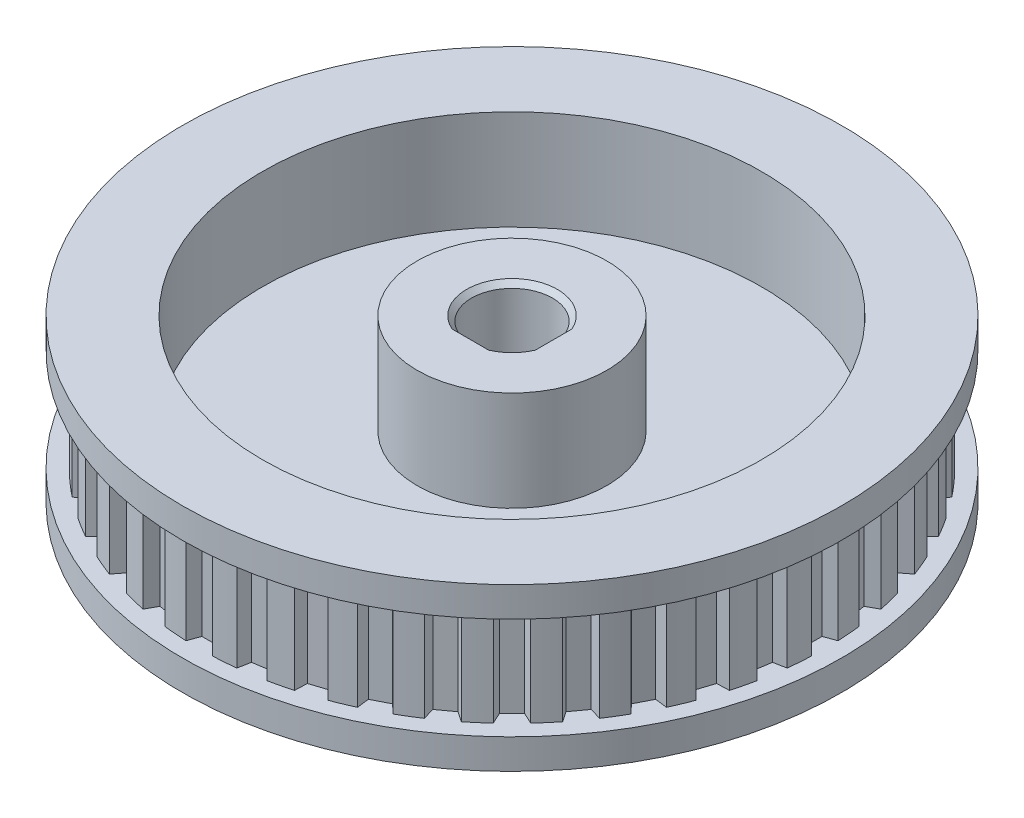
SolidWorks part; units mm, degrees
ref_plane "Спереди" through (0, 0, 0) normal (0, 0, 1) x (1, 0, 0)
ref_plane "Сверху" through (0, 0, 0) normal (0, 1, 0) x (1, 0, 0)
ref_plane "Справа" through (0, 0, 0) normal (1, 0, 0) x (0, 0, -1)
sketch "Эскиз1" plane through (0, 0, 0) normal (0, 1, 0) x (1, 0, 0)
  line L0 (0, 32.35) -> (0, 0) construction
  line L1 (-0.9, 30.15) -> (0.9, 30.15)
  line L2 (-0.9, 30.15) -> (-1.3265, 31.3219)
  line L3 (0.9, 30.15) -> (1.3265, 31.3219)
  line L4 (3.8276, 29.9196) -> (3.5896, 31.1438)
  line L5 (3.8276, 29.9196) -> (5.6054, 29.638)
  line L6 (5.6054, 29.638) -> (6.21, 30.7288)
  line L7 (8.4609, 28.9525) -> (8.4174, 30.1988)
  line L8 (8.4609, 28.9525) -> (10.1728, 28.3962)
  line L9 (10.1728, 28.3962) -> (10.9406, 29.379)
  line L10 (12.8859, 27.2724) -> (13.0379, 28.5103)
  line L11 (12.8859, 27.2724) -> (14.4897, 26.4553)
  line L12 (14.4897, 26.4553) -> (15.4018, 27.3058)
  line L13 (16.9936, 24.9209) -> (17.3374, 26.1197)
  line L14 (16.9936, 24.9209) -> (18.4498, 23.8629)
  line L15 (18.4498, 23.8629) -> (19.4838, 24.5602)
  line L16 (20.6829, 21.9557) -> (21.2099, 23.086)
  line L17 (20.6829, 21.9557) -> (21.9557, 20.6829)
  line L18 (21.9557, 20.6829) -> (23.086, 21.2099)
  line L19 (23.8629, 18.4498) -> (24.5602, 19.4838)
  line L20 (23.8629, 18.4498) -> (24.9209, 16.9936)
  line L21 (24.9209, 16.9936) -> (26.1197, 17.3374)
  line L22 (26.4553, 14.4897) -> (27.3058, 15.4018)
  line L23 (26.4553, 14.4897) -> (27.2724, 12.8859)
  line L24 (27.2724, 12.8859) -> (28.5103, 13.0379)
  line L25 (28.3962, 10.1728) -> (29.379, 10.9406)
  line L26 (28.3962, 10.1728) -> (28.9525, 8.4609)
  line L27 (28.9525, 8.4609) -> (30.1988, 8.4174)
  line L28 (29.638, 5.6054) -> (30.7288, 6.21)
  line L29 (29.638, 5.6054) -> (29.9196, 3.8276)
  line L30 (29.9196, 3.8276) -> (31.1438, 3.5896)
  line L31 (30.15, 0.9) -> (31.3219, 1.3265)
  line L32 (30.15, 0.9) -> (30.15, -0.9)
  line L33 (30.15, -0.9) -> (31.3219, -1.3265)
  line L34 (29.9196, -3.8276) -> (31.1438, -3.5896)
  line L35 (29.9196, -3.8276) -> (29.638, -5.6054)
  line L36 (29.638, -5.6054) -> (30.7288, -6.21)
  line L37 (28.9525, -8.4609) -> (30.1988, -8.4174)
  line L38 (28.9525, -8.4609) -> (28.3962, -10.1728)
  line L39 (28.3962, -10.1728) -> (29.379, -10.9406)
  line L40 (27.2724, -12.8859) -> (28.5103, -13.0379)
  line L41 (27.2724, -12.8859) -> (26.4553, -14.4897)
  line L42 (26.4553, -14.4897) -> (27.3058, -15.4018)
  line L43 (24.9209, -16.9936) -> (26.1197, -17.3374)
  line L44 (24.9209, -16.9936) -> (23.8629, -18.4498)
  line L45 (23.8629, -18.4498) -> (24.5602, -19.4838)
  line L46 (21.9557, -20.6829) -> (23.086, -21.2099)
  line L47 (21.9557, -20.6829) -> (20.6829, -21.9557)
  line L48 (20.6829, -21.9557) -> (21.2099, -23.086)
  line L49 (18.4498, -23.8629) -> (19.4838, -24.5602)
  line L50 (18.4498, -23.8629) -> (16.9936, -24.9209)
  line L51 (16.9936, -24.9209) -> (17.3374, -26.1197)
  line L52 (14.4897, -26.4553) -> (15.4018, -27.3058)
  line L53 (14.4897, -26.4553) -> (12.8859, -27.2724)
  line L54 (12.8859, -27.2724) -> (13.0379, -28.5103)
  line L55 (10.1728, -28.3962) -> (10.9406, -29.379)
  line L56 (10.1728, -28.3962) -> (8.4609, -28.9525)
  line L57 (8.4609, -28.9525) -> (8.4174, -30.1988)
  line L58 (5.6054, -29.638) -> (6.21, -30.7288)
  line L59 (5.6054, -29.638) -> (3.8276, -29.9196)
  line L60 (3.8276, -29.9196) -> (3.5896, -31.1438)
  line L61 (0.9, -30.15) -> (1.3265, -31.3219)
  line L62 (0.9, -30.15) -> (-0.9, -30.15)
  line L63 (-0.9, -30.15) -> (-1.3265, -31.3219)
  line L64 (-3.8276, -29.9196) -> (-3.5896, -31.1438)
  line L65 (-3.8276, -29.9196) -> (-5.6054, -29.638)
  line L66 (-5.6054, -29.638) -> (-6.21, -30.7288)
  line L67 (-8.4609, -28.9525) -> (-8.4174, -30.1988)
  line L68 (-8.4609, -28.9525) -> (-10.1728, -28.3962)
  line L69 (-10.1728, -28.3962) -> (-10.9406, -29.379)
  line L70 (-12.8859, -27.2724) -> (-13.0379, -28.5103)
  line L71 (-12.8859, -27.2724) -> (-14.4897, -26.4553)
  line L72 (-14.4897, -26.4553) -> (-15.4018, -27.3058)
  line L73 (-16.9936, -24.9209) -> (-17.3374, -26.1197)
  line L74 (-16.9936, -24.9209) -> (-18.4498, -23.8629)
  line L75 (-18.4498, -23.8629) -> (-19.4838, -24.5602)
  line L76 (-20.6829, -21.9557) -> (-21.2099, -23.086)
  line L77 (-20.6829, -21.9557) -> (-21.9557, -20.6829)
  line L78 (-21.9557, -20.6829) -> (-23.086, -21.2099)
  line L79 (-23.8629, -18.4498) -> (-24.5602, -19.4838)
  line L80 (-23.8629, -18.4498) -> (-24.9209, -16.9936)
  line L81 (-24.9209, -16.9936) -> (-26.1197, -17.3374)
  line L82 (-26.4553, -14.4897) -> (-27.3058, -15.4018)
  line L83 (-26.4553, -14.4897) -> (-27.2724, -12.8859)
  line L84 (-27.2724, -12.8859) -> (-28.5103, -13.0379)
  line L85 (-28.3962, -10.1728) -> (-29.379, -10.9406)
  line L86 (-28.3962, -10.1728) -> (-28.9525, -8.4609)
  line L87 (-28.9525, -8.4609) -> (-30.1988, -8.4174)
  line L88 (-29.638, -5.6054) -> (-30.7288, -6.21)
  line L89 (-29.638, -5.6054) -> (-29.9196, -3.8276)
  line L90 (-29.9196, -3.8276) -> (-31.1438, -3.5896)
  line L91 (-30.15, -0.9) -> (-31.3219, -1.3265)
  line L92 (-30.15, -0.9) -> (-30.15, 0.9)
  line L93 (-30.15, 0.9) -> (-31.3219, 1.3265)
  line L94 (-29.9196, 3.8276) -> (-31.1438, 3.5896)
  line L95 (-29.9196, 3.8276) -> (-29.638, 5.6054)
  line L96 (-29.638, 5.6054) -> (-30.7288, 6.21)
  line L97 (-28.9525, 8.4609) -> (-30.1988, 8.4174)
  line L98 (-28.9525, 8.4609) -> (-28.3962, 10.1728)
  line L99 (-28.3962, 10.1728) -> (-29.379, 10.9406)
  line L100 (-27.2724, 12.8859) -> (-28.5103, 13.0379)
  line L101 (-27.2724, 12.8859) -> (-26.4553, 14.4897)
  line L102 (-26.4553, 14.4897) -> (-27.3058, 15.4018)
  line L103 (-24.9209, 16.9936) -> (-26.1197, 17.3374)
  line L104 (-24.9209, 16.9936) -> (-23.8629, 18.4498)
  line L105 (-23.8629, 18.4498) -> (-24.5602, 19.4838)
  line L106 (-21.9557, 20.6829) -> (-23.086, 21.2099)
  line L107 (-21.9557, 20.6829) -> (-20.6829, 21.9557)
  line L108 (-20.6829, 21.9557) -> (-21.2099, 23.086)
  line L109 (-18.4498, 23.8629) -> (-19.4838, 24.5602)
  line L110 (-18.4498, 23.8629) -> (-16.9936, 24.9209)
  line L111 (-16.9936, 24.9209) -> (-17.3374, 26.1197)
  line L112 (-14.4897, 26.4553) -> (-15.4018, 27.3058)
  line L113 (-14.4897, 26.4553) -> (-12.8859, 27.2724)
  line L114 (-12.8859, 27.2724) -> (-13.0379, 28.5103)
  line L115 (-10.1728, 28.3962) -> (-10.9406, 29.379)
  line L116 (-10.1728, 28.3962) -> (-8.4609, 28.9525)
  line L117 (-8.4609, 28.9525) -> (-8.4174, 30.1988)
  line L118 (-5.6054, 29.638) -> (-6.21, 30.7288)
  line L119 (-5.6054, 29.638) -> (-3.8276, 29.9196)
  line L120 (-3.8276, 29.9196) -> (-3.5896, 31.1438)
  circle A0 centre (0, 0) radius 30.15 construction
  circle A1 centre (0, 0) radius 32.35 construction
  circle A2 centre (0, 0) radius 31.85 construction
  circle A3 centre (0, 0) radius 31.35 construction
  arc A4 (-3.5896, 31.1438) -> (-1.3265, 31.3219) centre (0, 0) cw
  arc A5 (1.3265, 31.3219) -> (3.5896, 31.1438) centre (0, 0) cw
  arc A6 (6.21, 30.7288) -> (8.4174, 30.1988) centre (0, 0) cw
  arc A7 (10.9406, 29.379) -> (13.0379, 28.5103) centre (0, 0) cw
  arc A8 (15.4018, 27.3058) -> (17.3374, 26.1197) centre (0, 0) cw
  arc A9 (19.4838, 24.5602) -> (21.2099, 23.086) centre (0, 0) cw
  arc A10 (23.086, 21.2099) -> (24.5602, 19.4838) centre (0, 0) cw
  arc A11 (26.1197, 17.3374) -> (27.3058, 15.4018) centre (0, 0) cw
  arc A12 (28.5103, 13.0379) -> (29.379, 10.9406) centre (0, 0) cw
  arc A13 (30.1988, 8.4174) -> (30.7288, 6.21) centre (0, 0) cw
  arc A14 (31.1438, 3.5896) -> (31.3219, 1.3265) centre (0, 0) cw
  arc A15 (31.3219, -1.3265) -> (31.1438, -3.5896) centre (0, 0) cw
  arc A16 (30.7288, -6.21) -> (30.1988, -8.4174) centre (0, 0) cw
  arc A17 (29.379, -10.9406) -> (28.5103, -13.0379) centre (0, 0) cw
  arc A18 (27.3058, -15.4018) -> (26.1197, -17.3374) centre (0, 0) cw
  arc A19 (24.5602, -19.4838) -> (23.086, -21.2099) centre (0, 0) cw
  arc A20 (21.2099, -23.086) -> (19.4838, -24.5602) centre (0, 0) cw
  arc A21 (17.3374, -26.1197) -> (15.4018, -27.3058) centre (0, 0) cw
  arc A22 (13.0379, -28.5103) -> (10.9406, -29.379) centre (0, 0) cw
  arc A23 (8.4174, -30.1988) -> (6.21, -30.7288) centre (0, 0) cw
  arc A24 (3.5896, -31.1438) -> (1.3265, -31.3219) centre (0, 0) cw
  arc A25 (-1.3265, -31.3219) -> (-3.5896, -31.1438) centre (0, 0) cw
  arc A26 (-6.21, -30.7288) -> (-8.4174, -30.1988) centre (0, 0) cw
  arc A27 (-10.9406, -29.379) -> (-13.0379, -28.5103) centre (0, 0) cw
  arc A28 (-15.4018, -27.3058) -> (-17.3374, -26.1197) centre (0, 0) cw
  arc A29 (-19.4838, -24.5602) -> (-21.2099, -23.086) centre (0, 0) cw
  arc A30 (-23.086, -21.2099) -> (-24.5602, -19.4838) centre (0, 0) cw
  arc A31 (-26.1197, -17.3374) -> (-27.3058, -15.4018) centre (0, 0) cw
  arc A32 (-28.5103, -13.0379) -> (-29.379, -10.9406) centre (0, 0) cw
  arc A33 (-30.1988, -8.4174) -> (-30.7288, -6.21) centre (0, 0) cw
  arc A34 (-31.1438, -3.5896) -> (-31.3219, -1.3265) centre (0, 0) cw
  arc A35 (-31.3219, 1.3265) -> (-31.1438, 3.5896) centre (0, 0) cw
  arc A36 (-30.7288, 6.21) -> (-30.1988, 8.4174) centre (0, 0) cw
  arc A37 (-29.379, 10.9406) -> (-28.5103, 13.0379) centre (0, 0) cw
  arc A38 (-27.3058, 15.4018) -> (-26.1197, 17.3374) centre (0, 0) cw
  arc A39 (-24.5602, 19.4838) -> (-23.086, 21.2099) centre (0, 0) cw
  arc A40 (-21.2099, 23.086) -> (-19.4838, 24.5602) centre (0, 0) cw
  arc A41 (-17.3374, 26.1197) -> (-15.4018, 27.3058) centre (0, 0) cw
  arc A42 (-13.0379, 28.5103) -> (-10.9406, 29.379) centre (0, 0) cw
  arc A43 (-8.4174, 30.1988) -> (-6.21, 30.7288) centre (0, 0) cw
  point P6 (0, 30.15)
  dimension "D1" = 63.7
  dimension "D2" = 64.7
  dimension "D3" = 60.3
  dimension "D4" = 62.7
  dimension "D5" = 1.8
  dimension "D6" = 20
  dimension "D7" = 20
extrude "Вытянуть1" add sketch "Эскиз1" along normal blind 10.2
sketch "Эскиз2" plane through (0, 10.2, 0) normal (0, 1, 0) x (1, 0, 0)
  circle A0 centre (0, 0) radius 33
  dimension "D1" = 66
extrude "Вытянуть2" add sketch "Эскиз2" along normal blind 3
sketch "Эскиз3" plane through (0, 0, 0) normal (0, -1, 0) x (1, 0, 0)
  circle A0 centre (0, 0) radius 33
  circle A1 centre (0, 0) radius 33 construction
extrude "Вытянуть3" add sketch "Эскиз3" along normal blind 3
sketch "Эскиз4" plane through (0, 13.2, 0) normal (0, 1, 0) x (1, 0, 0)
  circle A0 centre (0, 0) radius 25
  circle A1 centre (0, 0) radius 9.5
  dimension "D1" = 50
  dimension "D2" = 19
extrude "Вытянуть4" cut sketch "Эскиз4" against normal blind 10
sketch "Эскиз5" plane through (0, 13.2, 0) normal (0, 1, 0) x (1, 0, 0)
  line L0 (3.6643, 1.725) -> (3.6643, -1.725)
  line L1 (1.725, -3.6643) -> (-1.725, -3.6643)
  circle A0 centre (0, 0) radius 4.05 construction
  arc A1 (3.6643, 1.725) -> (-1.725, -3.6643) centre (0, 0) ccw
  arc A2 (1.725, -3.6643) -> (3.6643, -1.725) centre (0, 0) ccw
  dimension "D1" = 8.1
  dimension "D2" = 3.45
extrude "Вытянуть5" cut sketch "Эскиз5" against normal blind 10
sketch "Эскиз6" plane through (0, -3, 0) normal (0, -1, 0) x (1, 0, 0)
  circle A0 centre (0, 0) radius 4.05
  dimension "D1" = 8.1
extrude "Вытянуть6" cut sketch "Эскиз6" against normal up to surface (6.2 mm away) up to face at (0.9161, 3.2, 0.9161)
chamfer "Фаска1" distance 0.5 angle 45 1 edges at (0, -3, -4.05)
chamfer "Фаска2" distance 0.5 angle 45 4 edges at (0, 13.2, 3.6643) (-2.8638, 13.2, -2.8638) (2.8638, 13.2, 2.8638) (3.6643, 13.2, 0)
